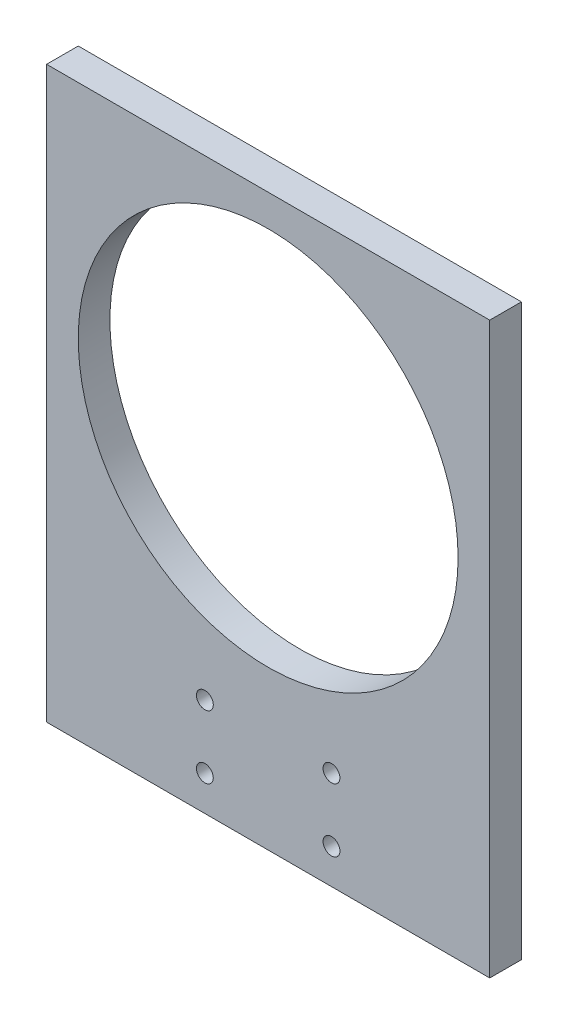
SolidWorks part; units mm, degrees
ref_plane "Front Plane" through (0, 0, 0) normal (0, 0, 1) x (1, 0, 0)
ref_plane "Top Plane" through (0, 0, 0) normal (0, 1, 0) x (1, 0, 0)
ref_plane "Right Plane" through (0, 0, 0) normal (1, 0, 0) x (0, 0, -1)
sketch "Sketch1" plane through (0, 0, 0) normal (0, 0, 1) x (1, 0, 0)
  line L0 (88.9, 0) -> (88.9, 14.0363)
  line L1 (0, 0) -> (177.8, 0)
  line L2 (0, 0) -> (0, 228.6)
  line L3 (0, 228.6) -> (177.8, 228.6)
  line L4 (177.8, 0) -> (177.8, 228.6)
  circle A0 centre (88.9, 139.7) radius 76.2
  circle A1 centre (63.5, 14.0363) radius 3.3782
  circle A2 centre (63.5, 39.4363) radius 3.3782
  circle A3 centre (114.3, 14.0363) radius 3.3782
  circle A4 centre (114.3, 39.4363) radius 3.3782
  dimension "D4" = 152.4
  dimension "D6" = 6.7564
  dimension "D7" = 6.7564
  dimension "D1" = 228.6
  dimension "D2" = 177.8
  dimension "D3" = 139.7
  dimension "D5" = 88.9
  dimension "D8" = 63.5
  dimension "D9" = 63.5
  dimension "D10" = 25.4
extrude "Boss-Extrude3" add sketch "Sketch1" along normal blind 12.7 contours L2 L1 L4 L3 | A0 | A2 | A1 | A4 | A3
